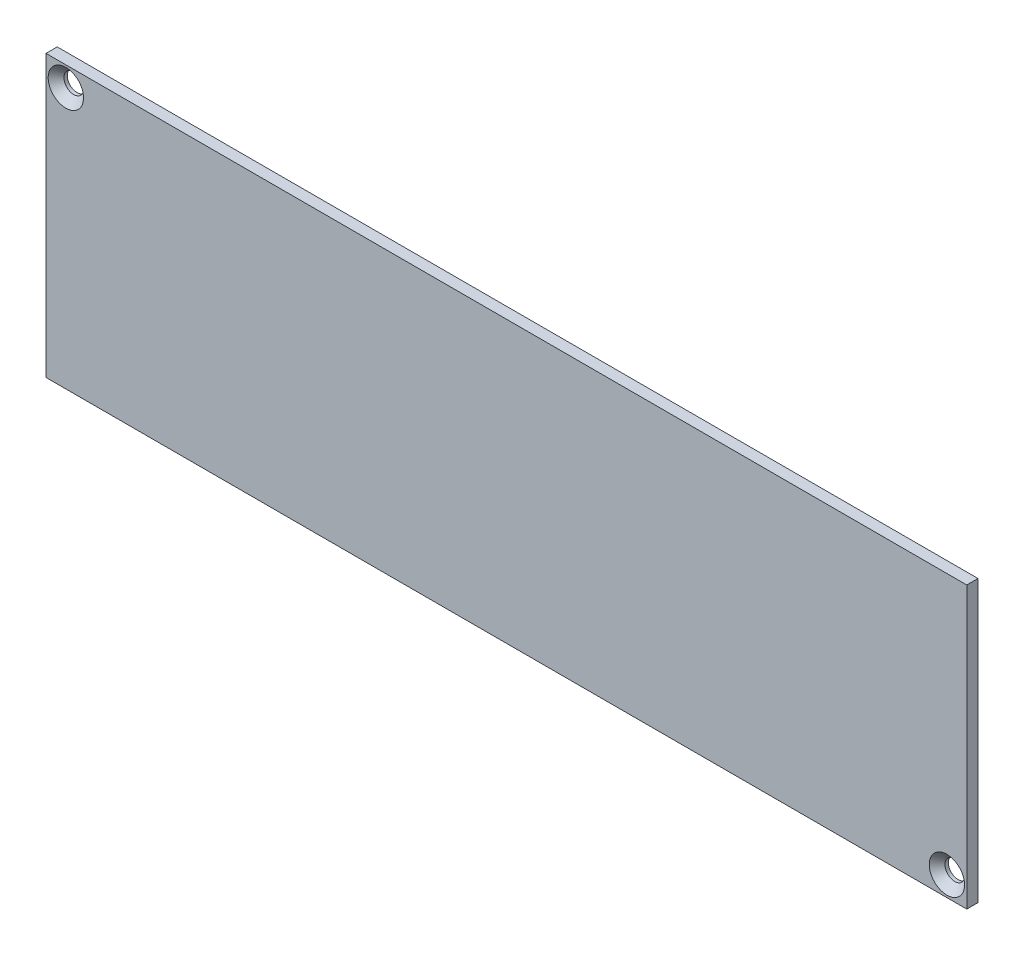
SolidWorks part; units mm, degrees
ref_plane "Front Plane" through (0, 0, 0) normal (0, 0, 1) x (1, 0, 0)
ref_plane "Top Plane" through (0, 0, 0) normal (0, 1, 0) x (1, 0, 0)
ref_plane "Right Plane" through (0, 0, 0) normal (1, 0, 0) x (0, 0, -1)
sketch "Sketch1" plane through (0, 0, 0) normal (0, 0, 1) x (1, 0, 0)
  line L0 (82, 14) -> (82, 25) construction
  line L1 (82, -25) -> (82, -14) construction
  line L2 (-82, -25) -> (82, -25) construction
  line L3 (-82, 25) -> (-82, -25) construction
  line L4 (82, 25) -> (-82, 25) construction
  line L5 (82, 14) -> (82, 25)
  line L6 (82, -25) -> (82, -14)
  line L7 (-82, -25) -> (82, -25)
  line L8 (-82, 25) -> (-82, -25)
  line L9 (82, 25) -> (-82, 25)
  line L10 (82, 14) -> (82, -14)
  circle A0 centre (78.4645, -21.4645) radius 1.75 construction
  circle A1 centre (-78.4645, 21.4645) radius 1.75 construction
  circle A2 centre (78.4645, -21.4645) radius 1.75
  circle A3 centre (-78.4645, 21.4645) radius 1.75
extrude "Boss-Extrude1" add sketch "Sketch1" along normal blind 2 contours L10 L6 L7 L8 L9 L5 | A3 | A2
hole_wizard "CSK for M3 Flat Head Machine Screw1" positions "3DSketch1" profile "Sketch2" countersink size "M3" standard "ANSI Metric" end condition through all
sketch3d "3DSketch1"
  line L0 (-78.4645, 21.4645, 2) -> (-78.4645, 21.4645, 0) construction
  line L1 (78.4645, -21.4645, 2) -> (78.4645, -21.4645, 0) construction
  point P0 (-78.4645, 21.4645, 2)
  point P4 (78.4645, -21.4645, 2)
sketch "Sketch2" plane through (-78.4645, 21.4645, 2) normal (1, 0, 0) x (0, -1, 0)
  line L0 (0, 0) -> (0, 2)
  line L1 (0, 2) -> (1.7, 2)
  line L2 (1.7, 2) -> (1.7, 1.45)
  line L3 (1.7, 1.45) -> (3.15, 0)
  line L5 (3.15, 0) -> (0, 0)
  line L6 (-1.7, 1.45) -> (-3.15, 0) construction
  line L11 (0, -6.35) -> (0, 107.95) construction
  dimension "Thru Hole Dia." = 3.4
  dimension "Thru Hole Depth" = 2
  dimension "Near C'Sink Dia." = 6.3
  dimension "Near C'Sink Angle" = 90
